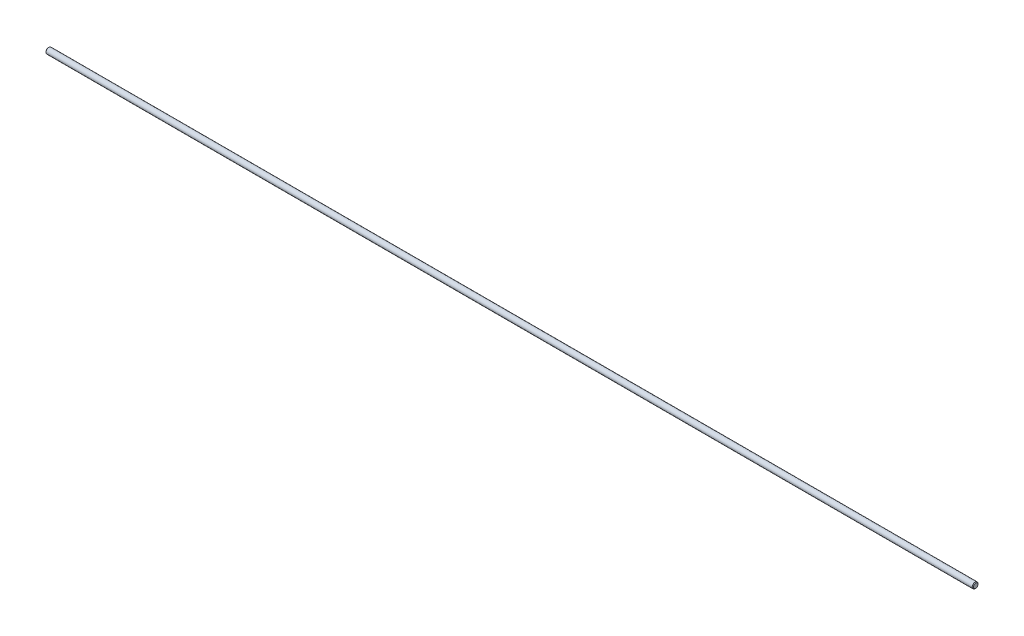
SolidWorks part; units mm, degrees
ref_plane "Front" through (0, 0, 0) normal (0, 0, 1) x (1, 0, 0)
ref_plane "Top" through (0, 0, 0) normal (0, 1, 0) x (1, 0, 0)
ref_plane "Right" through (0, 0, 0) normal (1, 0, 0) x (0, 0, -1)
sketch "Sketch1" plane through (0, 0, 0) normal (0, 0, 1) x (1, 0, 0)
  line L0 (-762, 0) -> (762, 0) construction
  line L1 (762, 4.7625) -> (762, -4.7625) construction
  line L2 (-762, 4.7625) -> (-762, -4.7625) construction
  dimension "Length" = 1524
  dimension "Diameter" = 9.525
sketch "Sketch2" plane through (0, 0, 0) normal (1, 0, 0) x (0, 0, -1)
  circle A0 centre (0, 0) radius 4.7625
extrude "Extrude1" add sketch "Sketch2" against normal up to vertex (762 mm away) and the other way up to vertex (762 mm away) up to point (-762, 4.7625, 0) other way up to point (762, 4.7625, 0)
chamfer "Chamfer1" distance 0.9525 angle 45 2 edges at (762, 0, -4.7625) (-762, 0, -4.7625)
equation "\"D1@Chamfer1\" = \"Diameter@Sketch1\"*.1"
